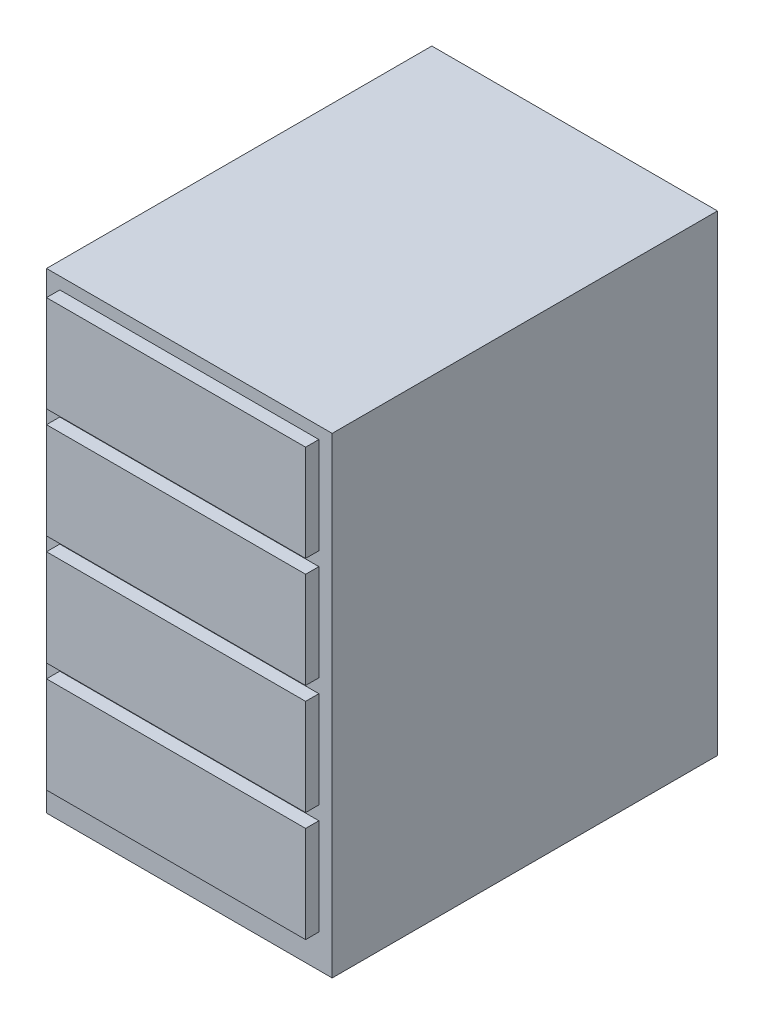
SolidWorks part; units mm, degrees
ref_plane "Plan de face" through (0, 0, 0) normal (0, 0, 1) x (1, 0, 0)
ref_plane "Plan de dessus" through (0, 0, 0) normal (0, 1, 0) x (1, 0, 0)
ref_plane "Plan de droite" through (0, 0, 0) normal (1, 0, 0) x (0, 0, -1)
sketch "Esquisse1" plane through (0, 0, 0) normal (0, 0, 1) x (1, 0, 0)
  line L1 (0, 0) -> (430, 0)
  line L2 (0, 0) -> (0, 710)
  line L3 (0, 710) -> (430, 710)
  line L4 (430, 0) -> (430, 710)
  dimension "D1" = 430
  dimension "D2" = 710
extrude "Boss.-Extru.1" add sketch "Esquisse1" along normal blind 580
sketch "Esquisse2" plane through (0, 0, 580) normal (0, 0, 1) x (1, 0, 0)
  line L0 (0, 371) -> (430, 371) construction
  line L1 (0, 710) -> (0, 0) construction
  line L2 (430, 0) -> (430, 710) construction
  line L3 (215, 360.6667) -> (215, 381.3333) construction
  line L4 (20, 526.3333) -> (410, 526.3333)
  line L5 (20, 526.3333) -> (20, 381.3333)
  line L6 (20, 381.3333) -> (410, 381.3333)
  line L7 (410, 526.3333) -> (410, 381.3333)
  line L8 (0, 536.6667) -> (430, 536.6667) construction
  line L9 (410, 547) -> (410, 692)
  line L10 (20, 692) -> (410, 692)
  line L11 (20, 547) -> (20, 692)
  line L12 (20, 547) -> (410, 547)
  line L13 (0, 205.3333) -> (430, 205.3333) construction
  line L14 (20, 195) -> (410, 195)
  line L15 (20, 195) -> (20, 50)
  line L16 (20, 50) -> (410, 50)
  line L17 (410, 195) -> (410, 50)
  line L18 (410, 215.6667) -> (410, 360.6667)
  line L19 (20, 360.6667) -> (410, 360.6667)
  line L20 (20, 215.6667) -> (20, 360.6667)
  line L21 (20, 215.6667) -> (410, 215.6667)
  line L22 (0, 0) -> (430, 0) construction
  line L23 (430, 710) -> (0, 710) construction
  line L24 (215, 195) -> (215, 215.6667) construction
  point P21 (215, 371)
  dimension "D1" = 145
  dimension "D2" = 20
  dimension "D3" = 50
  dimension "D4" = 18
extrude "Boss.-Extru.2" add sketch "Esquisse2" along normal blind 20
